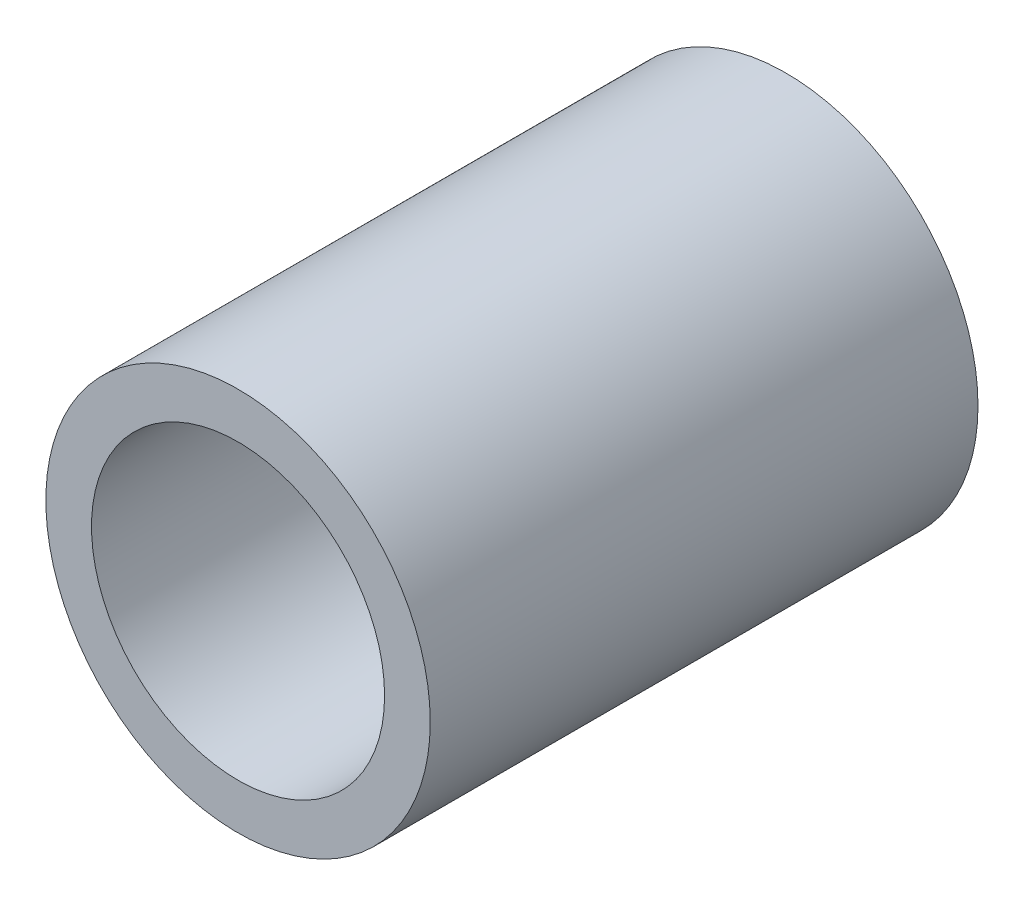
SolidWorks part; units mm, degrees
ref_plane "Front Plane" through (0, 0, 0) normal (0, 0, 1) x (1, 0, 0)
ref_plane "Top Plane" through (0, 0, 0) normal (0, 1, 0) x (1, 0, 0)
ref_plane "Right Plane" through (0, 0, 0) normal (1, 0, 0) x (0, 0, -1)
sketch "S01 - Installed brass envelope - simplified threads" plane through (0, 0, 0) normal (0, 0, 1) x (1, 0, 0)
  circle A0 centre (0, 0) radius 2
  circle A1 centre (0, 0) radius 1.525
extrude "01 - Installed brass envelope - simplified threads" add sketch "S01 - Installed brass envelope - simplified threads" along normal blind 5.7
